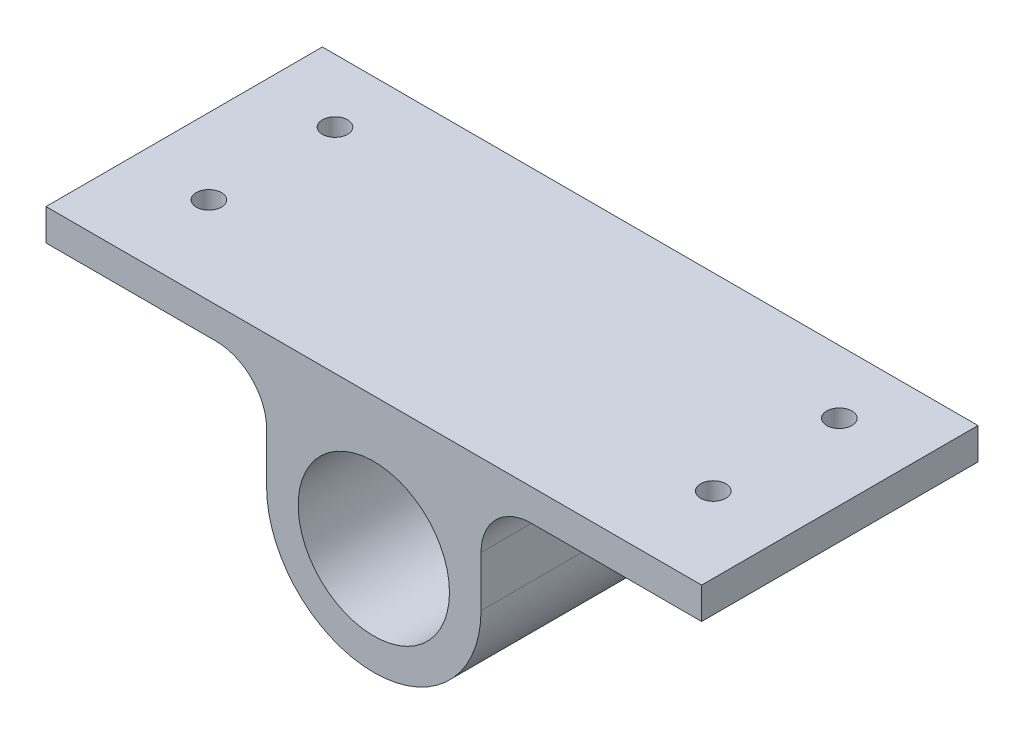
SolidWorks part; units mm, degrees
ref_plane "Front Plane" through (0, 0, 0) normal (0, 0, 1) x (1, 0, 0)
ref_plane "Top Plane" through (0, 0, 0) normal (0, 1, 0) x (1, 0, 0)
ref_plane "Right Plane" through (0, 0, 0) normal (1, 0, 0) x (0, 0, -1)
sketch "Sketch1" plane through (0, 0, 0) normal (0, 0, 1) x (1, 0, 0)
  line L1 (-82.55, 0) -> (-82.55, -7.9502)
  line L3 (82.55, 0) -> (82.55, -7.9502)
  line L10 (-82.55, 0) -> (82.55, 0)
  line L11 (-82.55, -7.9502) -> (-39.7002, -7.9502)
  line L13 (82.55, -7.9502) -> (39.7002, -7.9502)
  line L14 (27.0002, -20.6502) -> (27.0002, -60.3504)
  line L15 (27.0002, -60.3504) -> (-27.0002, -60.3504)
  line L17 (-27.0002, -20.6502) -> (-27.0002, -60.3504)
  circle A0 centre (0, -33.3502) radius 19.05
  arc A3 (-27.0002, -33.3502) -> (27.0002, -33.3502) centre (0, -33.3502) ccw
  arc A4 (39.7002, -7.9502) -> (27.0002, -20.6502) centre (39.7002, -20.6502) ccw
  arc A5 (-39.7002, -7.9502) -> (-27.0002, -20.6502) centre (-39.7002, -20.6502) cw
  point P13 (27.0002, -7.9502)
  point P16 (-27.0002, -7.9502)
  dimension "D3" = 38.1
  dimension "D5" = 33.3502
  dimension "D6" = 82.55
  dimension "D10" = 12.7
  dimension "D1" = 165.1
  dimension "D2" = 7.9502
  dimension "D4" = 27.0002
  dimension "D7" = 54.0004
  dimension "D8" = 52.4002
  dimension "D9" = 82.55
extrude "Boss-Extrude1" add sketch "Sketch1" along normal blind 69.596 contours L17 A3 L14 L13 L3 L10 L1 L11 A0
sketch "Sketch2" plane through (0, 0, 0) normal (0, 1, 0) x (1, 0, 0)
  line L0 (-82.55, 0) -> (82.55, 0) construction
  line L2 (63.5, -15.875) -> (63.5, -69.596) construction
  line L3 (-82.55, -69.596) -> (82.55, -69.596) construction
  line L4 (-82.55, -69.596) -> (-82.55, 0) construction
  line L5 (0, 0) -> (0, -69.596) construction
  circle A0 centre (63.5, -15.875) radius 3.175
  circle A1 centre (63.5, -47.625) radius 3.175
  circle A2 centre (-63.5, -47.625) radius 3.175
  circle A3 centre (-63.5, -15.875) radius 3.175
  dimension "D1" = 31.75
  dimension "D3" = 6.35
  dimension "D4" = 19.05
  dimension "D5" = 15.875
  dimension "D6" = 165.1
extrude "Cut-Extrude1" cut sketch "Sketch2" against normal blind 63.5
